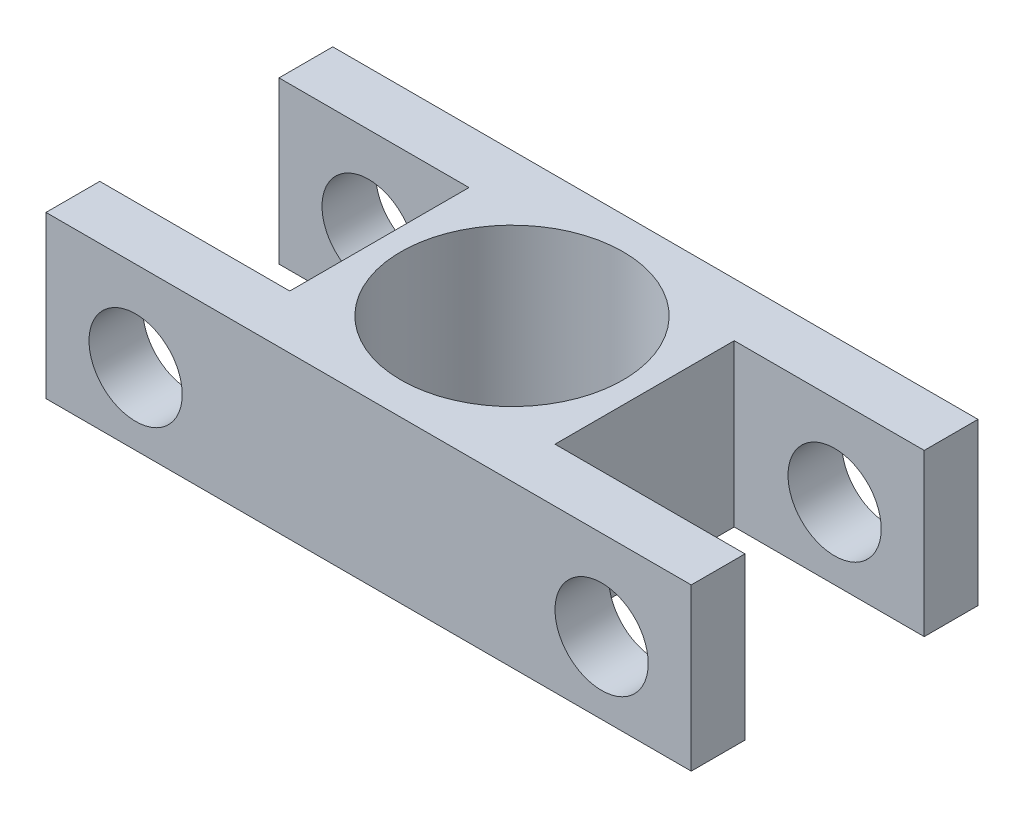
SolidWorks part; units mm, degrees
ref_plane "前视基准面" through (0, 0, 0) normal (0, 0, 1) x (1, 0, 0)
ref_plane "上视基准面" through (0, 0, 0) normal (0, 1, 0) x (1, 0, 0)
ref_plane "右视基准面" through (0, 0, 0) normal (1, 0, 0) x (0, 0, -1)
other "Configuration Table"
sketch "草图1" plane through (0, 0, 0) normal (0, 0, 1) x (1, 0, 0)
  line L0 (0, 0) -> (36, 0)
  line L1 (36, 0) -> (36, 9)
  line L2 (36, 9) -> (0, 9)
  line L3 (0, 9) -> (0, 0)
  dimension "width" = 36
  dimension "height" = 9
extrude "BlockExtrude" add sketch "草图1" along normal blind 16
ref_plane "Slot_midplane" through (0, 0, 8) normal (0, 0, 1) x (1, 0, 0)
sketch "草图3" plane through (0, 0, 8) normal (0, 0, 1) x (1, 0, 0)
  line L0 (-2, -2) -> (10.6, -2)
  line L1 (10.6, -2) -> (10.6, 11)
  line L2 (10.6, 11) -> (-2, 11)
  line L3 (-2, 11) -> (-2, -2)
  dimension "x0" = 2
  dimension "x1" = 10.6
  dimension "y0" = 2
  dimension "y2" = 11
extrude "Clevis_slot" cut sketch "草图3" against normal mid plane 10
sketch "草图4" plane through (0, 0, 8) normal (0, 0, 1) x (1, 0, 0)
  line L0 (25.4, -2) -> (38, -2)
  line L1 (38, -2) -> (38, 11)
  line L2 (38, 11) -> (25.4, 11)
  line L3 (25.4, 11) -> (25.4, -2)
  dimension "x0" = 25.4
  dimension "x1" = 38
  dimension "y0" = 2
  dimension "y2" = 11
extrude "切除-拉伸2" cut sketch "草图4" against normal mid plane 10
sketch "草图5" plane through (0, 0, 16) normal (0, 0, 1) x (1, 0, 0)
  circle A0 centre (5, 4) radius 2.6
  dimension "diameter" = 5.2
  dimension "x" = 5
  dimension "y" = 4
extrude "Pivot_bore" cut sketch "草图5" against normal through all
sketch "草图6" plane through (0, 0, 16) normal (0, 0, 1) x (1, 0, 0)
  circle A0 centre (31, 4) radius 2.6
  dimension "diameter" = 5.2
  dimension "x" = 31
  dimension "y" = 4
extrude "切除-拉伸4" cut sketch "草图6" against normal through all
sketch "草图7" plane through (0, 9, 0) normal (0, 1, 0) x (1, 0, 0)
  circle A0 centre (18, -8) radius 6.2
  dimension "diameter" = 12.4
  dimension "x" = 18
  dimension "y" = 8
extrude "Spindle_clearance" cut sketch "草图7" against normal through all
